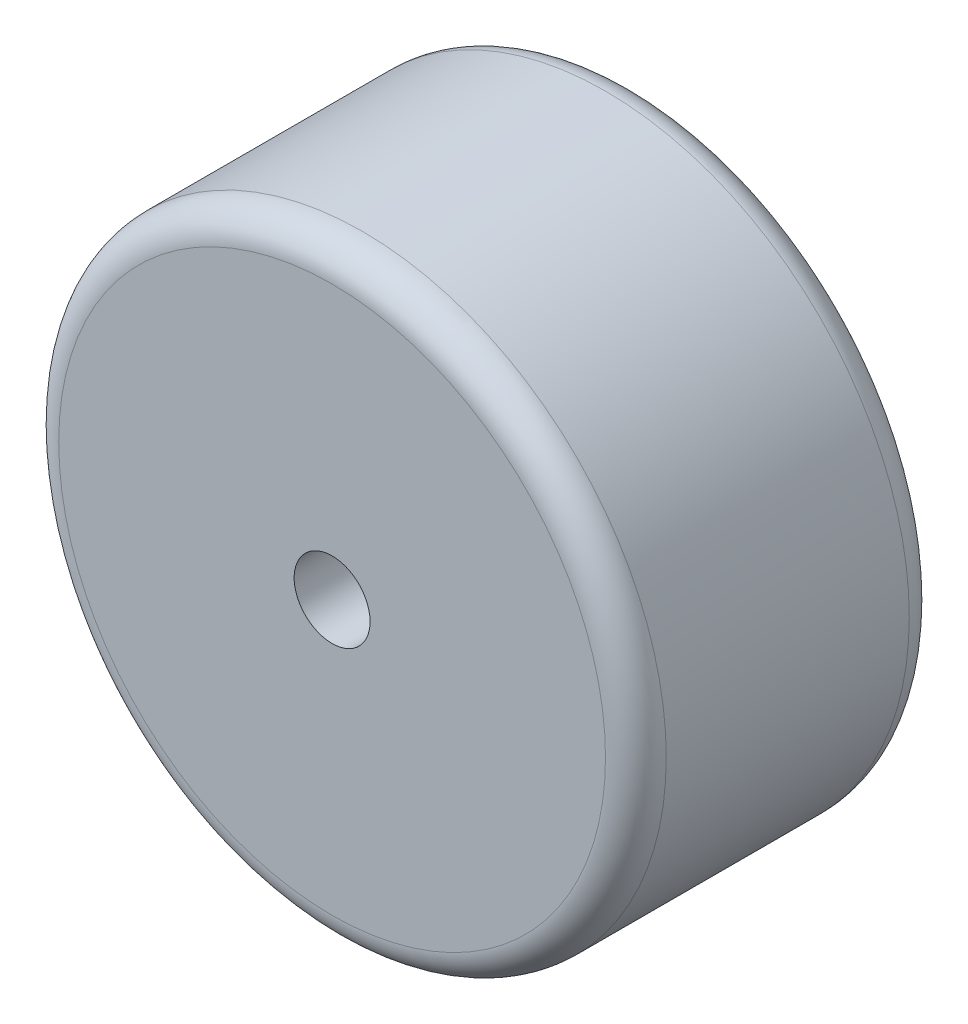
SolidWorks part; units mm, degrees
material "CA"
ref_plane "Front" through (0, 0, 0) normal (0, 0, 1) x (1, 0, 0)
ref_plane "Top" through (0, 0, 0) normal (0, 1, 0) x (1, 0, 0)
ref_plane "Right" through (0, 0, 0) normal (1, 0, 0) x (0, 0, -1)
sketch "Sketch1" plane through (0, 0, 0) normal (0, 0, 1) x (1, 0, 0)
  circle A0 centre (0, 0) radius 25.4
  dimension "D1" = 50.8
extrude "Boss-Extrude1" add sketch "Sketch1" along normal blind 25.4
fillet "Fillet1" radius 2.54 2 edges at (25.4, 0, 0) (25.4, 0, 25.4)
sketch "Sketch2" plane through (0, 0, 25.4) normal (0, 0, 1) x (1, 0, 0)
  circle A0 centre (0, 0) radius 3.175
  dimension "D1" = 6.35
extrude "Cut-Extrude1" cut sketch "Sketch2" against normal up to next
